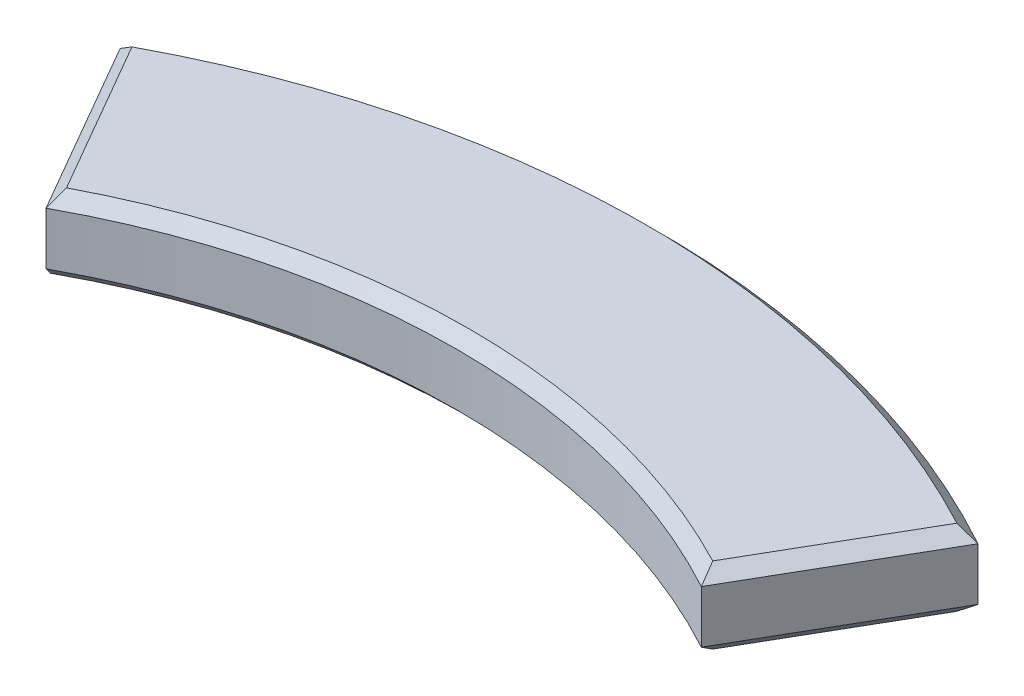
SolidWorks part; units mm, degrees
ref_plane "Front Plane" through (0, 0, 0) normal (0, 0, 1) x (1, 0, 0)
ref_plane "Top Plane" through (0, 0, 0) normal (0, 1, 0) x (1, 0, 0)
ref_plane "Right Plane" through (0, 0, 0) normal (1, 0, 0) x (0, 0, -1)
sketch "Sketch1" plane through (0, 0, 0) normal (0, 1, 0) x (1, 0, 0)
  line L0 (-14, 24.2487) -> (-19, 32.909) construction
  line L1 (14, 24.2487) -> (19, 32.909) construction
  line L2 (0, 0) -> (4, 0) construction
  line L3 (-17.9717, 32.6279) -> (-13.7293, 25.2798)
  line L4 (17.9717, 32.6279) -> (13.7293, 25.2798)
  line L5 (-16.5, 28.5788) -> (-15.8505, 28.9538) construction
  line L6 (15.8505, 28.9538) -> (16.5, 28.5788) construction
  circle A0 centre (0, 0) radius 28 construction
  circle A1 centre (0, 0) radius 38 construction
  arc A2 (-17.9717, 32.6279) -> (17.9717, 32.6279) centre (0, 0) cw
  arc A3 (-13.7293, 25.2798) -> (13.7293, 25.2798) centre (0, 0) cw
  point P19 (16.5, 28.5788)
  dimension "D1" = 28
  dimension "D2" = 38
  dimension "D4" = 0.75
  dimension "D6" = 60
  dimension "D3" = 60
  dimension "D5" = 0.75
extrude "Boss-Extrude1" add sketch "Sketch1" along normal blind 3.2
chamfer "Chamfer1" distance 0.5 angle 45 7 edges at (15.8505, 3.2, -28.9538) (0, 3.2, -37.25) (0, 3.2, -28.7673) (-15.8505, 3.2, -28.9538) (0, 0, -37.25) (15.8505, 0, -28.9538) (0, 0, -28.7673)
sketch "Sketch2" plane through (0, 0, 0) normal (0, -1, 0) x (1, 0, 0)
  line L0 (13.7293, -25.2798) -> (17.9717, -32.6279) construction
  line L3 (-17.7217, -32.1948) -> (-13.9793, -25.7129) construction
  circle A2 centre (0, -33) radius 1.625
  arc A3 (-15.8462, -28.9465) -> (15.8462, -28.9465) centre (0, 0) ccw construction
  dimension "D1" = 3.25
  dimension "D2" = 33
extrude "Cut-Extrude1" cut sketch "Sketch2" against normal blind 2
